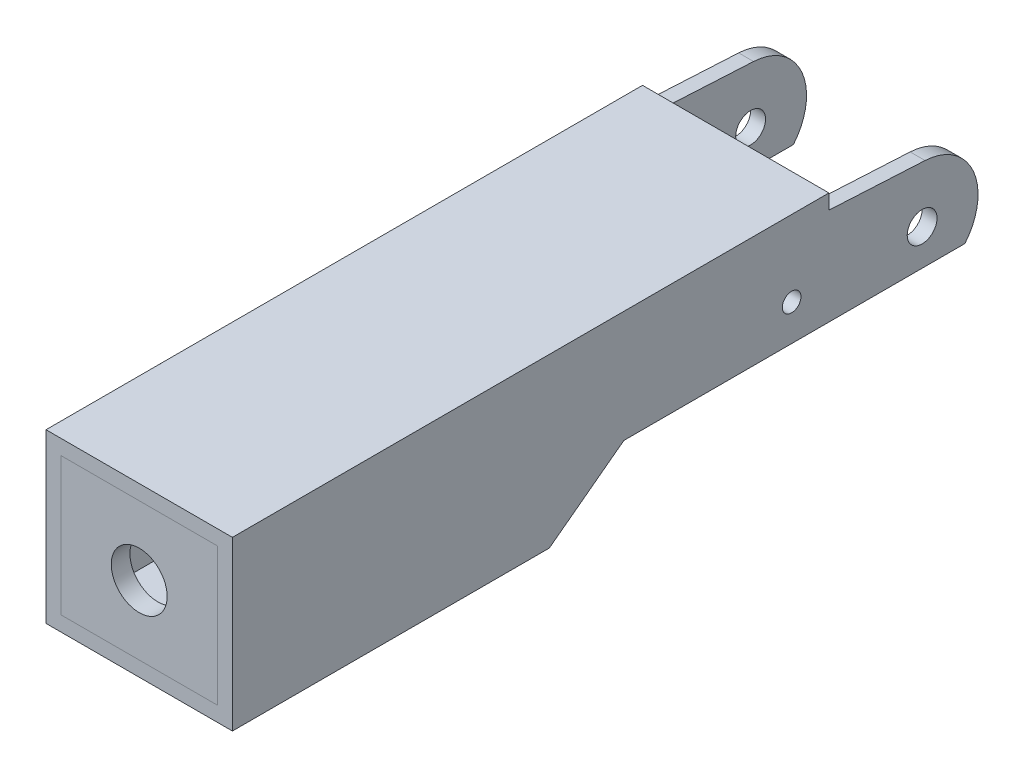
SolidWorks part; units mm, degrees
ref_plane "正面" through (0, 0, 0) normal (0, 0, 1) x (1, 0, 0)
ref_plane "平面" through (0, 0, 0) normal (0, 1, 0) x (1, 0, 0)
ref_plane "右側面" through (0, 0, 0) normal (1, 0, 0) x (0, 0, -1)
sketch "ｽｹｯﾁ1" plane through (0, 0, 0) normal (0, 0, 1) x (1, 0, 0)
  line L0 (4, -4) -> (4, -41)
  line L1 (0, 0) -> (50, 0)
  line L2 (0, 0) -> (0, -45)
  line L3 (0, -45) -> (50, -45)
  line L4 (50, 0) -> (50, -45)
  line L5 (4, -41) -> (46, -41)
  line L6 (46, -4) -> (46, -41)
  line L7 (4, -4) -> (46, -4)
  dimension "D1" = 50
  dimension "D2" = 45
  dimension "D3" = 4
extrude "ﾎﾞｽ - 押し出し1" add sketch "ｽｹｯﾁ1" along normal blind 200
sketch "ｽｹｯﾁ2" plane through (50, 0, 0) normal (1, 0, 0) x (0, 0, -1)
  line L1 (-200, 0) -> (0, 0) construction
  line L2 (0, -45) -> (0, 0) construction
  line L3 (-3.523, -30) -> (-95, -30)
  line L4 (-95, -30) -> (-115, -45)
  line L5 (-200, -45) -> (0, -45) construction
  line L6 (-40, 0) -> (-200, 0)
  line L7 (-200, 0) -> (-200, -45)
  line L8 (-200, -45) -> (-115, -45)
  line L9 (-15, -20.342) -> (-50, -20.342) construction
  line L10 (-14.2085, -5.3629) -> (-40, -4)
  line L11 (-40, -4) -> (-40, 0)
  arc A0 (-14.2085, -5.3629) -> (-3.523, -30) centre (-15, -20.342) cw
  circle A1 centre (-50, -20.342) radius 2.5
  circle A2 centre (-15, -20.342) radius 4
  dimension "D4" = 15
  dimension "D8" = 5
  dimension "D9" = 8
  dimension "D1" = 30
  dimension "D2" = 115
  dimension "D3" = 20
  dimension "D5" = 20.342
  dimension "D6" = 40
  dimension "D7" = 35
  dimension "D10" = 4
extrude "ｶｯﾄ - 押し出し1" cut sketch "ｽｹｯﾁ2" against normal through all flip side to cut
sketch "ｽｹｯﾁ3" plane through (0, 0, 200) normal (0, 0, 1) x (1, 0, 0)
  line L0 (46, -22.5) -> (4, -22.5) construction
  line L1 (4, -4) -> (46, -4)
  line L2 (4, -4) -> (4, -41)
  line L3 (4, -41) -> (46, -41)
  line L4 (46, -4) -> (46, -41)
  circle A0 centre (25, -22.5) radius 7.5
  point P10 (0, 0)
  dimension "D1" = 15
extrude "ﾎﾞｽ - 押し出し2" add sketch "ｽｹｯﾁ3" against normal blind 5 separate body
